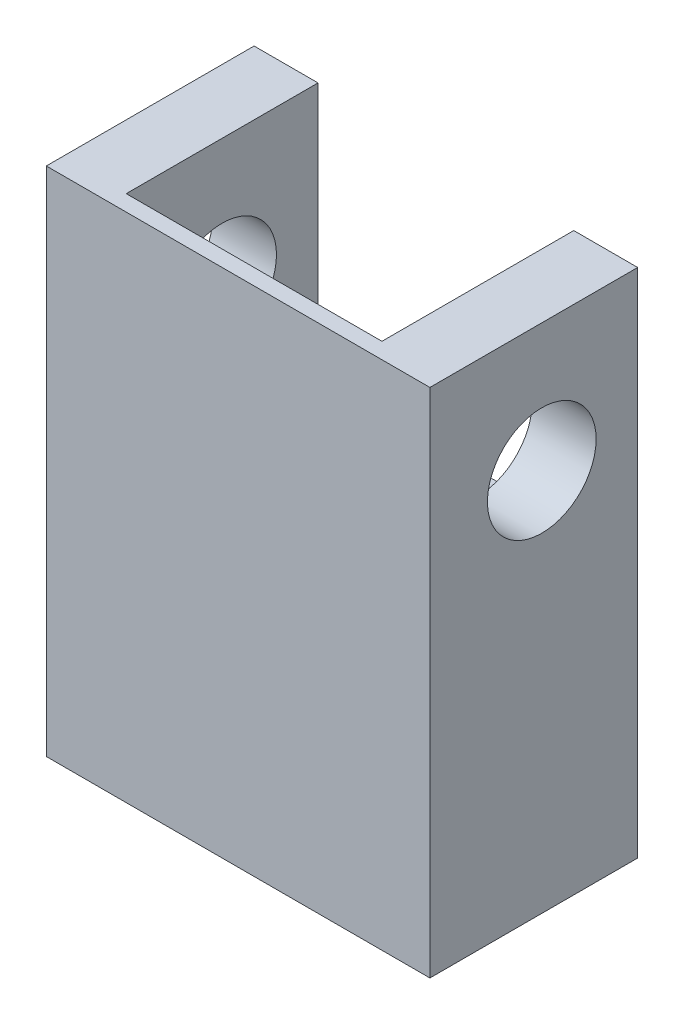
SolidWorks part; units mm, degrees
ref_plane "Front Plane" through (0, 0, 0) normal (0, 0, 1) x (1, 0, 0)
ref_plane "Top Plane" through (0, 0, 0) normal (0, 1, 0) x (1, 0, 0)
ref_plane "Right Plane" through (0, 0, 0) normal (1, 0, 0) x (0, 0, -1)
sketch "Sketch1" plane through (0, 0, 0) normal (0, 0, 1) x (1, 0, 0)
  line L0 (-38.1, 0) -> (38.1, 0)
  line L1 (38.1, 0) -> (38.1, 101.6)
  line L2 (38.1, 101.6) -> (25.4, 101.6)
  line L3 (25.4, 101.6) -> (25.4, 50.8)
  line L4 (25.4, 50.8) -> (-25.4, 50.8)
  line L5 (0, 50.8) -> (0, 0) construction
  line L6 (-25.4, 101.6) -> (-25.4, 50.8)
  line L7 (-38.1, 101.6) -> (-25.4, 101.6)
  line L8 (-38.1, 0) -> (-38.1, 101.6)
  dimension "D1" = 50.8
  dimension "D2" = 50.8
  dimension "D3" = 12.7
  dimension "D4" = 50.8
extrude "Boss-Extrude1" add sketch "Sketch1" along normal mid plane 38.1
sketch "Sketch2" plane through (0, 0, 0) normal (1, 0, 0) x (0, 0, -1)
  line L0 (-19.05, 101.6) -> (19.05, 101.6) construction
  circle A0 centre (0, 76.2) radius 10.795
  dimension "D1" = 21.59
  dimension "D2" = 25.4
extrude "Cut-Extrude1" cut sketch "Sketch2" against normal through all both and the other way through all
sketch "Sketch3" plane through (0, 0, 19.05) normal (0, 0, 1) x (1, 0, 0)
  line L1 (-38.1, 101.6) -> (38.1, 101.6)
  line L2 (-38.1, 101.6) -> (-38.1, 0)
  line L3 (-38.1, 0) -> (38.1, 0)
  line L4 (38.1, 101.6) -> (38.1, 0)
extrude "Boss-Extrude2" add sketch "Sketch3" along normal blind 3.175
